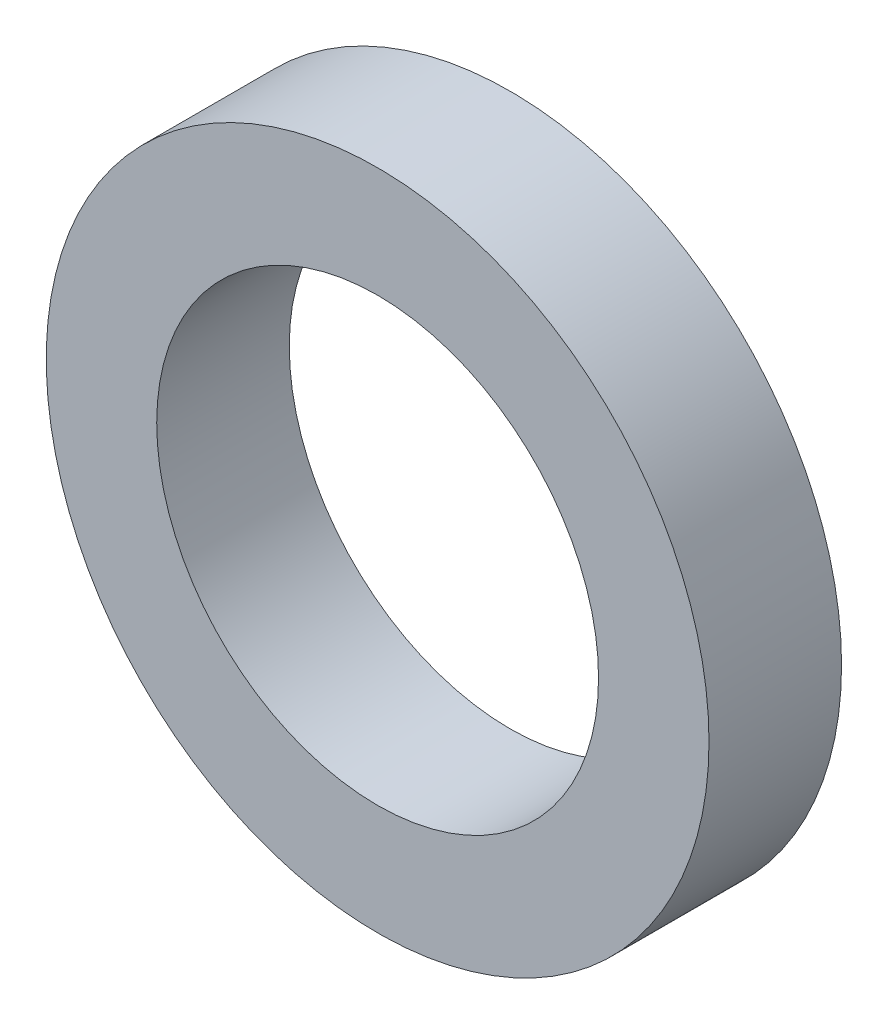
SolidWorks part; units mm, degrees
ref_plane "前视基准面" through (0, 0, 0) normal (0, 0, 1) x (1, 0, 0)
ref_plane "上视基准面" through (0, 0, 0) normal (0, 1, 0) x (1, 0, 0)
ref_plane "右视基准面" through (0, 0, 0) normal (1, 0, 0) x (0, 0, -1)
sketch "草图1" plane through (0, 0, 0) normal (0, 0, 1) x (1, 0, 0)
  circle A0 centre (0, 0) radius 5
  circle A1 centre (0, 0) radius 7.5
  dimension "D1" = 10
  dimension "D2" = 15
extrude "凸台-拉伸1" add sketch "草图1" along normal blind 3
